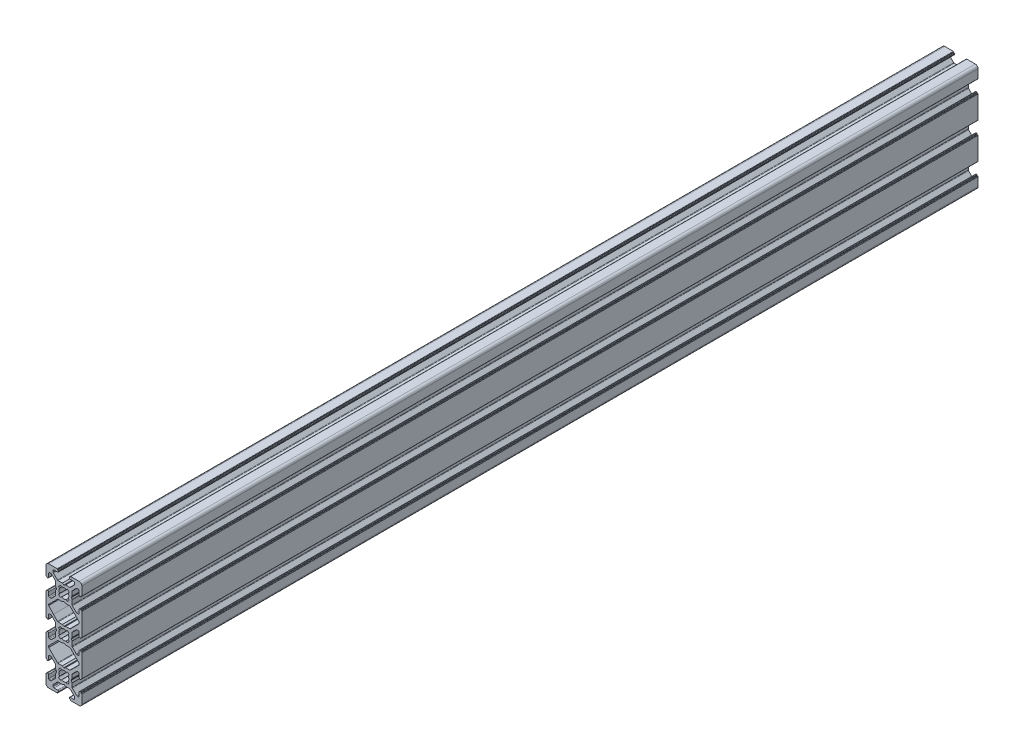
SolidWorks part; units mm, degrees
material "6061 Alloy"
ref_plane "Front Plane" through (0, 0, 0) normal (0, 0, 1) x (1, 0, 0)
ref_plane "Top Plane" through (0, 0, 0) normal (0, 1, 0) x (1, 0, 0)
ref_plane "Right Plane" through (0, 0, 0) normal (1, 0, 0) x (0, 0, -1)
sketch "Sketch2" plane through (0, 0, 0) normal (0, 0, 1) x (1, 0, 0)
  line L0 (0, -19.2121) -> (0, 56.5718) construction
  line L1 (8.5, 16.4558) -> (8.5, 14.5058)
  line L2 (10, 36.2558) -> (10, 23.6558)
  line L3 (-8.5, 30.4451) -> (-8.5, 29.884)
  line L4 (8.5, 30.4451) -> (8.5, 29.5607)
  line L5 (-3.5858, 4.6464) -> (-8.5, 9.5607)
  line L6 (-4.7214, 3.4608) -> (-7.1142, 5.8536)
  line L7 (-3.75, -10) -> (-8.5, -10)
  line L8 (-4.7214, -3.4608) -> (-7.1142, -5.8536)
  line L9 (-9.7, -3.55) -> (-9.8, -3.55)
  line L10 (-9.5, -3.2) -> (-9.5, -3.35)
  line L11 (-7.4678, -6) -> (-8, -6)
  line L12 (-9, -3) -> (-9.3, -3)
  line L13 (-8.5, -3.5) -> (-8.5, -5.5)
  line L14 (-10, -3.75) -> (-10, -8.5)
  line L15 (-7.4678, 6) -> (-8, 6)
  line L16 (-9.7, 3.55) -> (-9.8, 3.55)
  line L17 (-9.5, 3.2) -> (-9.5, 3.35)
  line L18 (-9, 3) -> (-9.3, 3)
  line L19 (-8.5, 3.5) -> (-8.5, 5.5)
  line L20 (-10, 16.2558) -> (-10, 3.75)
  line L21 (-4.575, -3.1072) -> (-4.575, -1.0835)
  line L22 (4.575, -3.1072) -> (4.575, -1.0835)
  line L23 (3.2322, -4.5) -> (0.9536, -4.5)
  line L24 (-3.2322, -4.5) -> (-0.9536, -4.5)
  line L25 (-0.8536, -4.4732) -> (-0.1, -4.0381)
  line L26 (0.8536, -4.4732) -> (0.1, -4.0381)
  line L27 (-3.5, -8.5) -> (-5.5, -8.5)
  line L28 (-3.2, -9.5) -> (-3.35, -9.5)
  line L29 (-3.55, -9.7) -> (-3.55, -9.8)
  line L30 (-6, -7.2678) -> (-6, -8)
  line L31 (-3.5858, -4.6464) -> (-5.8536, -6.9142)
  line L32 (-3, -9) -> (-3, -9.3)
  line L33 (3.55, -9.7) -> (3.55, -9.8)
  line L34 (3.2, -9.5) -> (3.35, -9.5)
  line L35 (6, -7.2678) -> (6, -8)
  line L36 (3, -9) -> (3, -9.3)
  line L37 (3.5, -8.5) -> (5.5, -8.5)
  line L38 (3.75, -10) -> (8.5, -10)
  line L39 (10, -3.7) -> (10, -8.5)
  line L40 (8.5, -3.5) -> (8.5, -5.5)
  line L41 (9.5, -3.2) -> (9.5, -3.3)
  line L42 (9.7, -3.5) -> (9.8, -3.5)
  line L43 (7.4678, -6) -> (8, -6)
  line L44 (4.7214, -3.4608) -> (7.1142, -5.8536)
  line L45 (3.5858, -4.6464) -> (5.8536, -6.9142)
  line L46 (9, -3) -> (9.3, -3)
  line L47 (3.5858, 4.6464) -> (8.5, 9.5607)
  line L48 (3.2322, 4.5) -> (0.9536, 4.5)
  line L49 (-3.2322, 4.5) -> (-0.9536, 4.5)
  line L50 (-0.8536, 4.4732) -> (-0.1, 4.0381)
  line L51 (0.8536, 4.4732) -> (0.1, 4.0381)
  line L52 (1.2582, 2.4453) -> (1.9099, 2.9922)
  line L53 (-4.575, 3.1072) -> (-4.575, 1.0835)
  line L54 (-4.5482, 0.9835) -> (-4.0381, 0.1)
  line L55 (-4.5482, -0.9835) -> (-4.0381, -0.1)
  line L56 (-1.2623, 2.4431) -> (-1.9139, 2.9896)
  line L57 (-2.4453, 1.2582) -> (-2.9922, 1.9099)
  line L58 (-2.4431, -1.2623) -> (-2.9897, -1.9139)
  line L59 (-1.2582, -2.4453) -> (-1.9099, -2.9922)
  line L60 (1.2623, -2.4431) -> (1.9139, -2.9897)
  line L61 (2.4453, 1.2582) -> (2.9896, 1.9139)
  line L62 (4.5482, -0.9835) -> (4.0381, -0.1)
  line L63 (4.5482, 0.9835) -> (4.0381, 0.1)
  line L64 (4.575, 3.1072) -> (4.575, 1.0835)
  line L65 (2.4453, -1.2582) -> (2.9922, -1.9099)
  line L66 (9.7, 3.5) -> (9.8, 3.5)
  line L67 (9.5, 3.2) -> (9.5, 3.3)
  line L68 (7.4678, 6) -> (8, 6)
  line L69 (9, 3) -> (9.3, 3)
  line L70 (8.5, 3.5) -> (8.5, 5.5)
  line L71 (10, 3.7) -> (10, 16.2558)
  line L72 (4.7214, 3.4608) -> (7.1142, 5.8536)
  line L73 (-4.7214, 36.345) -> (-6.9142, 34.1522)
  line L74 (-3.5858, 35.3593) -> (-8.5, 30.4451)
  line L75 (-4.7214, 43.6666) -> (-6.9142, 45.8593)
  line L76 (-3.75, 50) -> (-8.5, 50)
  line L77 (-10, 43.6558) -> (-10, 48.5)
  line L78 (-8.5, 43.4558) -> (-8.5, 45.5058)
  line L79 (0, 40.0058) -> (15.2221, 40.0058) construction
  line L80 (-8.5, 36.4558) -> (-8.5, 34.5058)
  line L81 (-9, 36.9558) -> (-9.3, 36.9558)
  line L82 (-7.2678, 34.0058) -> (-8, 34.0058)
  line L83 (-9.5, 36.7558) -> (-9.5, 36.6558)
  line L84 (-9.7, 36.4558) -> (-9.8, 36.4558)
  line L85 (-9, 42.9558) -> (-9.3, 42.9558)
  line L86 (-9.5, 43.1558) -> (-9.5, 43.2558)
  line L87 (-9.7, 43.4558) -> (-9.8, 43.4558)
  line L88 (-7.2678, 46.0058) -> (-8, 46.0058)
  line L89 (4.7214, 43.6666) -> (6.9142, 45.8593)
  line L90 (10, 43.6558) -> (10, 48.5)
  line L91 (8.5, 43.4558) -> (8.5, 45.5058)
  line L92 (3.5858, 35.3593) -> (8.5, 30.4451)
  line L93 (-4.7214, 16.345) -> (-6.9142, 14.1522)
  line L94 (3.2322, 35.5058) -> (0.9536, 35.5058)
  line L95 (1.2582, 37.5605) -> (1.8871, 37.0581)
  line L96 (-1.2582, 37.5605) -> (-1.8871, 37.0581)
  line L97 (-2.4453, 38.7476) -> (-2.9477, 38.1187)
  line L98 (-2.4453, 41.264) -> (-2.9477, 41.8928)
  line L99 (-1.2582, 42.4511) -> (-1.8871, 42.9535)
  line L100 (0.8536, 35.5326) -> (0.1, 35.9677)
  line L101 (-0.8536, 35.5326) -> (-0.1, 35.9677)
  line L102 (-3.2322, 35.5058) -> (-0.9536, 35.5058)
  line L103 (-4.575, 36.6986) -> (-4.575, 39.1772)
  line L104 (-4.5482, 39.2772) -> (-4.142, 39.9808)
  line L105 (-4.5482, 40.8844) -> (-4.142, 40.1808)
  line L106 (-4.575, 43.313) -> (-4.575, 40.9844)
  line L107 (1.2582, 42.4511) -> (1.8871, 42.9535)
  line L108 (9, 42.9558) -> (9.3, 42.9558)
  line L109 (9.5, 43.1558) -> (9.5, 43.2558)
  line L110 (9.7, 43.4558) -> (9.8, 43.4558)
  line L111 (9, 36.9558) -> (9.3, 36.9558)
  line L112 (4.7214, 36.345) -> (6.9142, 34.1522)
  line L113 (7.2678, 34.0058) -> (8, 34.0058)
  line L114 (9.7, 36.4558) -> (9.8, 36.4558)
  line L115 (9.5, 36.7558) -> (9.5, 36.6558)
  line L116 (8.5, 36.4558) -> (8.5, 34.5058)
  line L117 (2.4453, 38.7476) -> (2.9477, 38.1187)
  line L118 (4.575, 43.313) -> (4.575, 40.9844)
  line L119 (4.5482, 40.8844) -> (4.142, 40.1808)
  line L120 (4.5482, 39.2772) -> (4.142, 39.9808)
  line L121 (4.575, 36.6986) -> (4.575, 39.1772)
  line L122 (2.4453, 41.264) -> (2.9477, 41.8928)
  line L123 (3.2322, 44.5) -> (0.9536, 44.5)
  line L124 (-3.55, 49.7) -> (-3.55, 49.8)
  line L125 (-3.2, 49.5) -> (-3.35, 49.5)
  line L126 (-3.5858, 44.6464) -> (-5.8536, 46.9142)
  line L127 (-6, 47.2678) -> (-6, 48)
  line L128 (0.8536, 44.4732) -> (0.0592, 44.0146)
  line L129 (-0.8536, 44.4732) -> (-0.0592, 44.0146)
  line L130 (-3.2322, 44.5) -> (-0.9536, 44.5)
  line L131 (-3, 49) -> (-3, 49.3)
  line L132 (-3.5, 48.5) -> (-5.5, 48.5)
  line L133 (3, 49) -> (3, 49.3)
  line L134 (3.5858, 44.6464) -> (5.8536, 46.9142)
  line L135 (6, 47.2678) -> (6, 48)
  line L136 (3.55, 49.7) -> (3.55, 49.8)
  line L137 (3.2, 49.5) -> (3.35, 49.5)
  line L138 (3.5, 48.5) -> (5.5, 48.5)
  line L139 (3.75, 50) -> (8.5, 50)
  line L140 (-34.2612, 0) -> (36.5039, 0) construction
  line L141 (-3.5858, 15.3593) -> (-8.5, 10.4451)
  line L142 (-4.7214, 23.6666) -> (-6.9142, 25.8593)
  line L143 (-8.5, 10.4451) -> (-8.5, 9.5607)
  line L144 (-9.5, 16.7558) -> (-9.5, 16.6558)
  line L145 (-9.7, 16.4558) -> (-9.8, 16.4558)
  line L146 (-9, 16.9558) -> (-9.3, 16.9558)
  line L147 (-7.2678, 14.0058) -> (-8, 14.0058)
  line L148 (-5.8536, 26.9142) -> (-8.5, 29.884)
  line L149 (-8.5, 16.4558) -> (-8.5, 14.5058)
  line L150 (-9.8, 23.4558) -> (-9.7, 23.4558)
  line L151 (-9, 22.9558) -> (-9.3, 22.9558)
  line L152 (-9.5, 23.1558) -> (-9.5, 23.2558)
  line L153 (-7.2678, 26.0058) -> (-8, 26.0058)
  line L154 (7.2678, 26.0058) -> (8, 26.0058)
  line L155 (4.7214, 23.6666) -> (6.9142, 25.8593)
  line L156 (-10, 36.2558) -> (-10, 23.6558)
  line L157 (8.5, 25.5058) -> (8.5, 23.4558)
  line L158 (3.5858, 15.3593) -> (8.5, 10.4451)
  line L159 (3.2322, 15.5058) -> (0.9536, 15.5058)
  line L160 (1.2582, 17.5605) -> (1.8871, 17.0581)
  line L161 (-1.2582, 17.5605) -> (-1.8871, 17.0581)
  line L162 (-2.4453, 18.7476) -> (-2.9477, 18.1187)
  line L163 (-2.4453, 21.264) -> (-2.9477, 21.8928)
  line L164 (-1.2582, 22.4511) -> (-1.8871, 22.9535)
  line L165 (0.8536, 15.5326) -> (0.1, 15.9677)
  line L166 (-0.8536, 15.5326) -> (-0.1, 15.9677)
  line L167 (-3.2322, 15.5058) -> (-0.9536, 15.5058)
  line L168 (-4.575, 16.6986) -> (-4.575, 19.1772)
  line L169 (-4.5482, 19.2772) -> (-4.142, 19.9808)
  line L170 (-4.5482, 20.8844) -> (-4.142, 20.1808)
  line L171 (-4.575, 23.313) -> (-4.575, 20.9844)
  line L172 (1.2582, 22.4511) -> (1.8871, 22.9535)
  line L173 (9, 22.9558) -> (9.3, 22.9558)
  line L174 (9.5, 23.1558) -> (9.5, 23.2558)
  line L175 (9.8, 23.4558) -> (9.7, 23.4558)
  line L176 (9, 16.9558) -> (9.3, 16.9558)
  line L177 (4.7214, 16.345) -> (6.9142, 14.1522)
  line L178 (7.2678, 14.0058) -> (8, 14.0058)
  line L179 (9.7, 16.4558) -> (9.8, 16.4558)
  line L180 (9.5, 16.7558) -> (9.5, 16.6558)
  line L181 (5.8536, 26.9142) -> (8.5, 29.5607)
  line L182 (2.4453, 18.7476) -> (2.9477, 18.1187)
  line L183 (4.575, 23.313) -> (4.575, 20.9844)
  line L184 (4.5482, 20.8844) -> (4.142, 20.1808)
  line L185 (4.5482, 19.2772) -> (4.142, 19.9808)
  line L186 (4.575, 16.6986) -> (4.575, 19.1772)
  line L187 (2.4453, 21.264) -> (2.9477, 21.8928)
  line L188 (3.2322, 24.5) -> (0.9536, 24.5)
  line L191 (-3.5858, 24.6464) -> (-5.8536, 26.9142)
  line L192 (-8.5, 25.5058) -> (-8.5, 23.4558)
  line L193 (0.8536, 24.4732) -> (0.0592, 24.0146)
  line L194 (-0.8536, 24.4732) -> (-0.0592, 24.0146)
  line L195 (-3.2322, 24.5) -> (-0.9536, 24.5)
  line L196 (8.5, 10.4451) -> (8.5, 9.5607)
  line L199 (3.5858, 24.6464) -> (5.8536, 26.9142)
  line L206 (0, 20.0058) -> (15.2221, 20.0058) construction
  line L279 (7.2678, 46.0058) -> (8, 46.0058)
  line L280 (-3.75, 30) -> (-8.5, 30) [skipped]
  line L281 (-3.55, 29.7) -> (-3.55, 29.8) [skipped]
  line L282 (-3.2, 29.5) -> (-3.35, 29.5) [skipped]
  line L283 (-3, 29) -> (-3, 29.3) [skipped]
  line L284 (-3.5, 28.5) -> (-5.5, 28.5) [skipped]
  line L285 (-6, 27.2678) -> (-6, 28) [skipped]
  line L286 (3.5, 28.5) -> (5.5, 28.5) [skipped]
  line L287 (3, 29) -> (3, 29.3) [skipped]
  line L288 (3.75, 30) -> (8.5, 30) [skipped]
  line L289 (3.55, 29.7) -> (3.55, 29.8) [skipped]
  line L290 (3.2, 29.5) -> (3.35, 29.5) [skipped]
  line L291 (6, 27.2678) -> (6, 28) [skipped]
  line L292 (10, 23.6558) -> (10, 28.5) [skipped]
  line L293 (8.5, 16.4558) -> (8.5, 14.5058) [skipped]
  line L294 (-7.2678, 14.0058) -> (-8, 14.0058) [skipped]
  line L295 (-10, 23.6558) -> (-10, 28.5) [skipped]
  line L296 (-9.7, 23.4558) -> (-9.8, 23.4558) [skipped]
  line L297 (-7.2678, 26.0058) -> (-8, 26.0058) [skipped]
  line L298 (-8.5, 23.4558) -> (-8.5, 25.5058) [skipped]
  line L299 (-8.5, 16.4558) -> (-8.5, 14.5058) [skipped]
  line L300 (-9, 16.9558) -> (-9.3, 16.9558) [skipped]
  line L301 (-9.5, 16.7558) -> (-9.5, 16.6558) [skipped]
  line L302 (-9.7, 16.4558) -> (-9.8, 16.4558) [skipped]
  line L303 (9, 22.9558) -> (9.3, 22.9558) [skipped]
  line L304 (9.5, 23.1558) -> (9.5, 23.2558) [skipped]
  line L305 (9.7, 23.4558) -> (9.8, 23.4558) [skipped]
  line L306 (7.2678, 26.0058) -> (8, 26.0058) [skipped]
  line L307 (8.5, 23.4558) -> (8.5, 25.5058) [skipped]
  arc A0 (-5.8536, -6.9142) -> (-6, -7.2678) centre (-5.5, -7.2678) ccw
  arc A1 (-6, -8) -> (-5.5, -8.5) centre (-5.5, -8) ccw
  arc A2 (-8.5, -3.5) -> (-9, -3) centre (-9, -3.5) ccw
  arc A3 (-9.7, -3.55) -> (-9.5, -3.35) centre (-9.7, -3.35) ccw
  arc A4 (-9.8, -3.55) -> (-10, -3.75) centre (-9.8, -3.75) ccw
  arc A5 (-9.3, -3) -> (-9.5, -3.2) centre (-9.3, -3.2) ccw
  arc A6 (-7.4678, -6) -> (-7.1142, -5.8536) centre (-7.4678, -5.5) ccw
  arc A7 (-10, -8.5) -> (-8.5, -10) centre (-8.5, -8.5) ccw
  arc A8 (-8.5, -5.5) -> (-8, -6) centre (-8, -5.5) ccw
  arc A9 (-8, 6) -> (-8.5, 5.5) centre (-8, 5.5) ccw
  arc A10 (-7.1142, 5.8536) -> (-7.4678, 6) centre (-7.4678, 5.5) ccw
  arc A11 (-9.5, 3.35) -> (-9.7, 3.55) centre (-9.7, 3.35) ccw
  arc A12 (-10, 3.75) -> (-9.8, 3.55) centre (-9.8, 3.75) ccw
  arc A13 (-9.5, 3.2) -> (-9.3, 3) centre (-9.3, 3.2) ccw
  arc A14 (-9, 3) -> (-8.5, 3.5) centre (-9, 3.5) ccw
  arc A15 (9, -3) -> (8.5, -3.5) centre (9, -3.5) ccw
  arc A16 (-4.7214, -3.4608) -> (-4.575, -3.1072) centre (-5.075, -3.1072) ccw
  arc A17 (-3.2322, -4.5) -> (-3.5858, -4.6464) centre (-3.2322, -5) ccw
  arc A18 (0.8536, -4.4732) -> (0.9536, -4.5) centre (0.9536, -4.3) ccw
  arc A19 (-0.9536, -4.5) -> (-0.8536, -4.4732) centre (-0.9536, -4.3) ccw
  arc A20 (0.1, -4.0381) -> (-0.1, -4.0381) centre (0, -4.2113) ccw
  arc A21 (-3.2, -9.5) -> (-3, -9.3) centre (-3.2, -9.3) ccw
  arc A22 (-3.75, -10) -> (-3.55, -9.8) centre (-3.75, -9.8) ccw
  arc A23 (-3.35, -9.5) -> (-3.55, -9.7) centre (-3.35, -9.7) ccw
  arc A24 (-3, -9) -> (-3.5, -8.5) centre (-3.5, -9) ccw
  arc A25 (3.5858, -4.6464) -> (3.2322, -4.5) centre (3.2322, -5) ccw
  arc A26 (4.575, -3.1072) -> (4.7214, -3.4608) centre (5.075, -3.1072) ccw
  arc A27 (3.55, -9.7) -> (3.35, -9.5) centre (3.35, -9.7) ccw
  arc A28 (3.55, -9.8) -> (3.75, -10) centre (3.75, -9.8) ccw
  arc A29 (3, -9.3) -> (3.2, -9.5) centre (3.2, -9.3) ccw
  arc A30 (6, -7.2678) -> (5.8536, -6.9142) centre (5.5, -7.2678) ccw
  arc A31 (8.5, -10) -> (10, -8.5) centre (8.5, -8.5) ccw
  arc A32 (5.5, -8.5) -> (6, -8) centre (5.5, -8) ccw
  arc A33 (9.5, -3.2) -> (9.3, -3) centre (9.3, -3.2) ccw
  arc A34 (10, -3.7) -> (9.8, -3.5) centre (9.8, -3.7) ccw
  arc A35 (9.5, -3.3) -> (9.7, -3.5) centre (9.7, -3.3) ccw
  arc A36 (7.1142, -5.8536) -> (7.4678, -6) centre (7.4678, -5.5) ccw
  arc A37 (8, -6) -> (8.5, -5.5) centre (8, -5.5) ccw
  arc A38 (3.5, -8.5) -> (3, -9) centre (3.5, -9) ccw
  arc A39 (2.9896, 1.9139) -> (1.9099, 2.9922) centre (0, 0) ccw
  arc A40 (1.9139, -2.9897) -> (2.9922, -1.9099) centre (0, 0) ccw
  arc A41 (1.2582, 2.4453) -> (-1.2623, 2.4431) centre (0, 0) ccw
  arc A42 (-0.1, 4.0381) -> (0.1, 4.0381) centre (0, 4.2113) ccw
  arc A43 (0.9536, 4.5) -> (0.8536, 4.4732) centre (0.9536, 4.3) ccw
  arc A44 (-0.8536, 4.4732) -> (-0.9536, 4.5) centre (-0.9536, 4.3) ccw
  arc A45 (-3.5858, 4.6464) -> (-3.2322, 4.5) centre (-3.2322, 5) ccw
  arc A46 (-4.575, 3.1072) -> (-4.7214, 3.4608) centre (-5.075, 3.1072) ccw
  arc A47 (-4.5482, -0.9835) -> (-4.575, -1.0835) centre (-4.375, -1.0835) ccw
  arc A48 (-4.575, 1.0835) -> (-4.5482, 0.9835) centre (-4.375, 1.0835) ccw
  arc A49 (-4.0381, -0.1) -> (-4.0381, 0.1) centre (-4.2113, 0) ccw
  arc A50 (-1.9139, 2.9896) -> (-2.9922, 1.9099) centre (0, 0) ccw
  arc A51 (-2.9897, -1.9139) -> (-1.9099, -2.9922) centre (0, 0) ccw
  arc A52 (-2.4453, 1.2582) -> (-2.4431, -1.2623) centre (0, 0) ccw
  arc A53 (-1.2582, -2.4453) -> (1.2623, -2.4431) centre (0, 0) ccw
  arc A54 (3.2322, 4.5) -> (3.5858, 4.6464) centre (3.2322, 5) ccw
  arc A55 (4.7214, 3.4608) -> (4.575, 3.1072) centre (5.075, 3.1072) ccw
  arc A56 (4.5482, 0.9835) -> (4.575, 1.0835) centre (4.375, 1.0835) ccw
  arc A57 (4.575, -1.0835) -> (4.5482, -0.9835) centre (4.375, -1.0835) ccw
  arc A58 (4.0381, 0.1) -> (4.0381, -0.1) centre (4.2113, 0) ccw
  arc A59 (2.4453, -1.2582) -> (2.4453, 1.2582) centre (0, 0) ccw
  arc A60 (9.7, 3.5) -> (9.5, 3.3) centre (9.7, 3.3) ccw
  arc A61 (9.8, 3.5) -> (10, 3.7) centre (9.8, 3.7) ccw
  arc A62 (9.3, 3) -> (9.5, 3.2) centre (9.3, 3.2) ccw
  arc A63 (7.4678, 6) -> (7.1142, 5.8536) centre (7.4678, 5.5) ccw
  arc A64 (8.5, 5.5) -> (8, 6) centre (8, 5.5) ccw
  arc A65 (8.5, 3.5) -> (9, 3) centre (9, 3.5) ccw
  arc A66 (-6, 47.2678) -> (-5.8536, 46.9142) centre (-5.5, 47.2678) ccw
  arc A67 (-5.5, 48.5) -> (-6, 48) centre (-5.5, 48) ccw
  arc A68 (-9, 42.9558) -> (-8.5, 43.4558) centre (-9, 43.4558) ccw
  arc A69 (-8.5, 36.4558) -> (-9, 36.9558) centre (-9, 36.4558) ccw
  arc A70 (-8.5, 34.5058) -> (-8, 34.0058) centre (-8, 34.5058) ccw
  arc A71 (-7.2678, 34.0058) -> (-6.9142, 34.1522) centre (-7.2678, 34.5058) ccw
  arc A72 (-9.3, 36.9558) -> (-9.5, 36.7558) centre (-9.3, 36.7558) ccw
  arc A73 (-9.8, 36.4558) -> (-10, 36.2558) centre (-9.8, 36.2558) ccw
  arc A74 (-9.7, 36.4558) -> (-9.5, 36.6558) centre (-9.7, 36.6558) ccw
  arc A75 (-9.5, 43.1558) -> (-9.3, 42.9558) centre (-9.3, 43.1558) ccw
  arc A76 (-10, 43.6558) -> (-9.8, 43.4558) centre (-9.8, 43.6558) ccw
  arc A77 (-9.5, 43.2558) -> (-9.7, 43.4558) centre (-9.7, 43.2558) ccw
  arc A78 (-6.9142, 45.8593) -> (-7.2678, 46.0058) centre (-7.2678, 45.5058) ccw
  arc A79 (-8, 46.0058) -> (-8.5, 45.5058) centre (-8, 45.5058) ccw
  arc A80 (-8.5, 50) -> (-10, 48.5) centre (-8.5, 48.5) ccw
  arc A81 (1.8871, 37.0581) -> (2.9477, 38.1187) centre (0, 40.0058) ccw
  arc A82 (2.9477, 41.8928) -> (1.8871, 42.9535) centre (0, 40.0058) ccw
  arc A83 (-1.2582, 37.5605) -> (1.2582, 37.5605) centre (0, 40.0058) ccw
  arc A84 (-2.4453, 41.264) -> (-2.4453, 38.7476) centre (0, 40.0058) ccw
  arc A85 (-2.9477, 38.1187) -> (-1.8871, 37.0581) centre (0, 40.0058) ccw
  arc A86 (-1.8871, 42.9535) -> (-2.9477, 41.8928) centre (0, 40.0058) ccw
  arc A87 (0.1, 35.9677) -> (-0.1, 35.9677) centre (0, 35.7945) ccw
  arc A88 (-0.9536, 35.5058) -> (-0.8536, 35.5326) centre (-0.9536, 35.7058) ccw
  arc A89 (0.8536, 35.5326) -> (0.9536, 35.5058) centre (0.9536, 35.7058) ccw
  arc A90 (-3.2322, 35.5058) -> (-3.5858, 35.3593) centre (-3.2322, 35.0058) ccw
  arc A91 (-4.142, 39.9808) -> (-4.142, 40.1808) centre (-4.3152, 40.0808) ccw
  arc A92 (-4.575, 40.9844) -> (-4.5482, 40.8844) centre (-4.375, 40.9844) ccw
  arc A93 (-4.5482, 39.2772) -> (-4.575, 39.1772) centre (-4.375, 39.1772) ccw
  arc A94 (-4.575, 43.313) -> (-4.7214, 43.6666) centre (-5.075, 43.313) ccw
  arc A95 (-4.7214, 36.345) -> (-4.575, 36.6986) centre (-5.075, 36.6986) ccw
  arc A96 (1.2582, 42.4511) -> (-1.2582, 42.4511) centre (0, 40.0058) ccw
  arc A97 (9, 36.9558) -> (8.5, 36.4558) centre (9, 36.4558) ccw
  arc A98 (8.5, 43.4558) -> (9, 42.9558) centre (9, 43.4558) ccw
  arc A99 (9.3, 42.9558) -> (9.5, 43.1558) centre (9.3, 43.1558) ccw
  arc A100 (9.8, 43.4558) -> (10, 43.6558) centre (9.8, 43.6558) ccw
  arc A101 (9.7, 43.4558) -> (9.5, 43.2558) centre (9.7, 43.2558) ccw
  arc A102 (8, 34.0058) -> (8.5, 34.5058) centre (8, 34.5058) ccw
  arc A103 (6.9142, 34.1522) -> (7.2678, 34.0058) centre (7.2678, 34.5058) ccw
  arc A104 (9.5, 36.6558) -> (9.7, 36.4558) centre (9.7, 36.6558) ccw
  arc A105 (10, 36.2558) -> (9.8, 36.4558) centre (9.8, 36.2558) ccw
  arc A106 (9.5, 36.7558) -> (9.3, 36.9558) centre (9.3, 36.7558) ccw
  arc A107 (2.4453, 38.7476) -> (2.4453, 41.264) centre (0, 40.0058) ccw
  arc A108 (4.142, 40.1808) -> (4.142, 39.9808) centre (4.3152, 40.0808) ccw
  arc A109 (4.575, 39.1772) -> (4.5482, 39.2772) centre (4.375, 39.1772) ccw
  arc A110 (4.5482, 40.8844) -> (4.575, 40.9844) centre (4.375, 40.9844) ccw
  arc A111 (4.575, 36.6986) -> (4.7214, 36.345) centre (5.075, 36.6986) ccw
  arc A112 (4.7214, 43.6666) -> (4.575, 43.313) centre (5.075, 43.313) ccw
  arc A113 (3.5858, 35.3593) -> (3.2322, 35.5058) centre (3.2322, 35.0058) ccw
  arc A114 (-3.5, 48.5) -> (-3, 49) centre (-3.5, 49) ccw
  arc A115 (-3.55, 49.7) -> (-3.35, 49.5) centre (-3.35, 49.7) ccw
  arc A116 (-3.55, 49.8) -> (-3.75, 50) centre (-3.75, 49.8) ccw
  arc A117 (-3, 49.3) -> (-3.2, 49.5) centre (-3.2, 49.3) ccw
  arc A118 (-3.5858, 44.6464) -> (-3.2322, 44.5) centre (-3.2322, 45) ccw
  arc A119 (-0.8536, 44.4732) -> (-0.9536, 44.5) centre (-0.9536, 44.3) ccw
  arc A120 (0.9536, 44.5) -> (0.8536, 44.4732) centre (0.9536, 44.3) ccw
  arc A121 (-0.0592, 44.0146) -> (0.0592, 44.0146) centre (0, 44.1171) ccw
  arc A122 (3, 49) -> (3.5, 48.5) centre (3.5, 49) ccw
  arc A123 (6, 48) -> (5.5, 48.5) centre (5.5, 48) ccw
  arc A124 (5.8536, 46.9142) -> (6, 47.2678) centre (5.5, 47.2678) ccw
  arc A125 (3.35, 49.5) -> (3.55, 49.7) centre (3.35, 49.7) ccw
  arc A126 (3.75, 50) -> (3.55, 49.8) centre (3.75, 49.8) ccw
  arc A127 (3.2, 49.5) -> (3, 49.3) centre (3.2, 49.3) ccw
  arc A128 (8.5, 45.5058) -> (8, 46.0058) centre (8, 45.5058) ccw
  arc A129 (10, 48.5) -> (8.5, 50) centre (8.5, 48.5) ccw
  arc A130 (7.2678, 46.0058) -> (6.9142, 45.8593) centre (7.2678, 45.5058) ccw
  arc A131 (3.2322, 44.5) -> (3.5858, 44.6464) centre (3.2322, 45) ccw
  arc A132 (-7.2678, 26.0058) -> (-6.9142, 25.8593) centre (-7.2678, 25.5058) cw
  arc A133 (-9.5, 16.7558) -> (-9.3, 16.9558) centre (-9.3, 16.7558) cw
  arc A134 (-9, 22.9558) -> (-8.5, 23.4558) centre (-9, 23.4558) ccw
  arc A135 (-10, 16.2558) -> (-9.8, 16.4558) centre (-9.8, 16.2558) cw
  arc A136 (-9.5, 16.6558) -> (-9.7, 16.4558) centre (-9.7, 16.6558) cw
  arc A137 (-7.2678, 14.0058) -> (-6.9142, 14.1522) centre (-7.2678, 14.5058) ccw
  arc A138 (-9, 16.9558) -> (-8.5, 16.4558) centre (-9, 16.4558) cw
  arc A139 (-8, 14.0058) -> (-8.5, 14.5058) centre (-8, 14.5058) cw
  arc A140 (8, 26.0058) -> (8.5, 25.5058) centre (8, 25.5058) cw
  arc A141 (-9.5, 23.1558) -> (-9.3, 22.9558) centre (-9.3, 23.1558) ccw
  arc A142 (-10, 23.6558) -> (-9.8, 23.4558) centre (-9.8, 23.6558) ccw
  arc A143 (-9.5, 23.2558) -> (-9.7, 23.4558) centre (-9.7, 23.2558) ccw
  arc A144 (9, 22.9558) -> (8.5, 23.4558) centre (9, 23.4558) cw
  arc A145 (-8, 26.0058) -> (-8.5, 25.5058) centre (-8, 25.5058) ccw
  arc A146 (9.5, 23.1558) -> (9.3, 22.9558) centre (9.3, 23.1558) cw
  arc A147 (1.8871, 17.0581) -> (2.9477, 18.1187) centre (0, 20.0058) ccw
  arc A148 (2.9477, 21.8928) -> (1.8871, 22.9535) centre (0, 20.0058) ccw
  arc A149 (-1.2582, 17.5605) -> (1.2582, 17.5605) centre (0, 20.0058) ccw
  arc A150 (-2.4453, 21.264) -> (-2.4453, 18.7476) centre (0, 20.0058) ccw
  arc A151 (-2.9477, 18.1187) -> (-1.8871, 17.0581) centre (0, 20.0058) ccw
  arc A152 (-1.8871, 22.9535) -> (-2.9477, 21.8928) centre (0, 20.0058) ccw
  arc A153 (0.1, 15.9677) -> (-0.1, 15.9677) centre (0, 15.7945) ccw
  arc A154 (-0.9536, 15.5058) -> (-0.8536, 15.5326) centre (-0.9536, 15.7058) ccw
  arc A155 (0.8536, 15.5326) -> (0.9536, 15.5058) centre (0.9536, 15.7058) ccw
  arc A156 (-3.2322, 15.5058) -> (-3.5858, 15.3593) centre (-3.2322, 15.0058) ccw
  arc A157 (-4.142, 19.9808) -> (-4.142, 20.1808) centre (-4.3152, 20.0808) ccw
  arc A158 (-4.575, 20.9844) -> (-4.5482, 20.8844) centre (-4.375, 20.9844) ccw
  arc A159 (-4.5482, 19.2772) -> (-4.575, 19.1772) centre (-4.375, 19.1772) ccw
  arc A160 (-4.575, 23.313) -> (-4.7214, 23.6666) centre (-5.075, 23.313) ccw
  arc A161 (-4.7214, 16.345) -> (-4.575, 16.6986) centre (-5.075, 16.6986) ccw
  arc A162 (1.2582, 22.4511) -> (-1.2582, 22.4511) centre (0, 20.0058) ccw
  arc A163 (9, 16.9558) -> (8.5, 16.4558) centre (9, 16.4558) ccw
  arc A164 (9.5, 23.2558) -> (9.7, 23.4558) centre (9.7, 23.2558) cw
  arc A165 (10, 23.6558) -> (9.8, 23.4558) centre (9.8, 23.6558) cw
  arc A168 (8, 14.0058) -> (8.5, 14.5058) centre (8, 14.5058) ccw
  arc A169 (6.9142, 14.1522) -> (7.2678, 14.0058) centre (7.2678, 14.5058) ccw
  arc A170 (9.5, 16.6558) -> (9.7, 16.4558) centre (9.7, 16.6558) ccw
  arc A171 (10, 16.2558) -> (9.8, 16.4558) centre (9.8, 16.2558) ccw
  arc A172 (9.5, 16.7558) -> (9.3, 16.9558) centre (9.3, 16.7558) ccw
  arc A173 (2.4453, 18.7476) -> (2.4453, 21.264) centre (0, 20.0058) ccw
  arc A174 (4.142, 20.1808) -> (4.142, 19.9808) centre (4.3152, 20.0808) ccw
  arc A175 (4.575, 19.1772) -> (4.5482, 19.2772) centre (4.375, 19.1772) ccw
  arc A176 (4.5482, 20.8844) -> (4.575, 20.9844) centre (4.375, 20.9844) ccw
  arc A177 (4.575, 16.6986) -> (4.7214, 16.345) centre (5.075, 16.6986) ccw
  arc A178 (4.7214, 23.6666) -> (4.575, 23.313) centre (5.075, 23.313) ccw
  arc A179 (3.5858, 15.3593) -> (3.2322, 15.5058) centre (3.2322, 15.0058) ccw
  arc A184 (-3.5858, 24.6464) -> (-3.2322, 24.5) centre (-3.2322, 25) ccw
  arc A185 (-0.8536, 24.4732) -> (-0.9536, 24.5) centre (-0.9536, 24.3) ccw
  arc A186 (0.9536, 24.5) -> (0.8536, 24.4732) centre (0.9536, 24.3) ccw
  arc A187 (-0.0592, 24.0146) -> (0.0592, 24.0146) centre (0, 24.1171) ccw
  arc A196 (7.2678, 26.0058) -> (6.9142, 25.8593) centre (7.2678, 25.5058) ccw
  arc A197 (3.2322, 24.5) -> (3.5858, 24.6464) centre (3.2322, 25) ccw
  arc A198 (-8.5, 30) -> (-10, 28.5) centre (-8.5, 28.5) ccw [skipped]
  arc A199 (-3, 29.3) -> (-3.2, 29.5) centre (-3.2, 29.3) ccw [skipped]
  arc A200 (-3.5, 28.5) -> (-3, 29) centre (-3.5, 29) ccw [skipped]
  arc A201 (-3.55, 29.7) -> (-3.35, 29.5) centre (-3.35, 29.7) ccw [skipped]
  arc A202 (-3.55, 29.8) -> (-3.75, 30) centre (-3.75, 29.8) ccw [skipped]
  arc A203 (-5.5, 28.5) -> (-6, 28) centre (-5.5, 28) ccw [skipped]
  arc A204 (-6, 27.2678) -> (-5.8536, 26.9142) centre (-5.5, 27.2678) ccw [skipped]
  arc A205 (3, 29) -> (3.5, 28.5) centre (3.5, 29) ccw [skipped]
  arc A206 (3.35, 29.5) -> (3.55, 29.7) centre (3.35, 29.7) ccw [skipped]
  arc A207 (3.2, 29.5) -> (3, 29.3) centre (3.2, 29.3) ccw [skipped]
  arc A208 (3.75, 30) -> (3.55, 29.8) centre (3.75, 29.8) ccw [skipped]
  arc A209 (6, 28) -> (5.5, 28.5) centre (5.5, 28) ccw [skipped]
  arc A210 (5.8536, 26.9142) -> (6, 27.2678) centre (5.5, 27.2678) ccw [skipped]
  arc A211 (10, 28.5) -> (8.5, 30) centre (8.5, 28.5) ccw [skipped]
  arc A212 (-6.9142, 25.8593) -> (-7.2678, 26.0058) centre (-7.2678, 25.5058) ccw [skipped]
  arc A213 (-8.5, 16.4558) -> (-9, 16.9558) centre (-9, 16.4558) ccw [skipped]
  arc A214 (-8.5, 14.5058) -> (-8, 14.0058) centre (-8, 14.5058) ccw [skipped]
  arc A215 (-9.3, 16.9558) -> (-9.5, 16.7558) centre (-9.3, 16.7558) ccw [skipped]
  arc A216 (-9.8, 16.4558) -> (-10, 16.2558) centre (-9.8, 16.2558) ccw [skipped]
  arc A217 (-9.7, 16.4558) -> (-9.5, 16.6558) centre (-9.7, 16.6558) ccw [skipped]
  arc A218 (8.5, 23.4558) -> (9, 22.9558) centre (9, 23.4558) ccw [skipped]
  arc A219 (9.3, 22.9558) -> (9.5, 23.1558) centre (9.3, 23.1558) ccw [skipped]
  arc A220 (9.8, 23.4558) -> (10, 23.6558) centre (9.8, 23.6558) ccw [skipped]
  arc A221 (9.7, 23.4558) -> (9.5, 23.2558) centre (9.7, 23.2558) ccw [skipped]
  arc A222 (8.5, 25.5058) -> (8, 26.0058) centre (8, 25.5058) ccw [skipped]
  dimension "D3" = 5.5
  dimension "D6" = 5.5
  dimension "D1" = 60
  dimension "D2" = 20
  dimension "D4" = 6
  dimension "D5" = 6
  dimension "D7" = 12
  dimension "D8" = 12
  dimension "D9" = 12
  dimension "D10" = 12
  dimension "D11" = 12
  dimension "D12" = 12
  dimension "D13" = 2
extrude "Extrude1" add sketch "Sketch2" along normal blind 500
